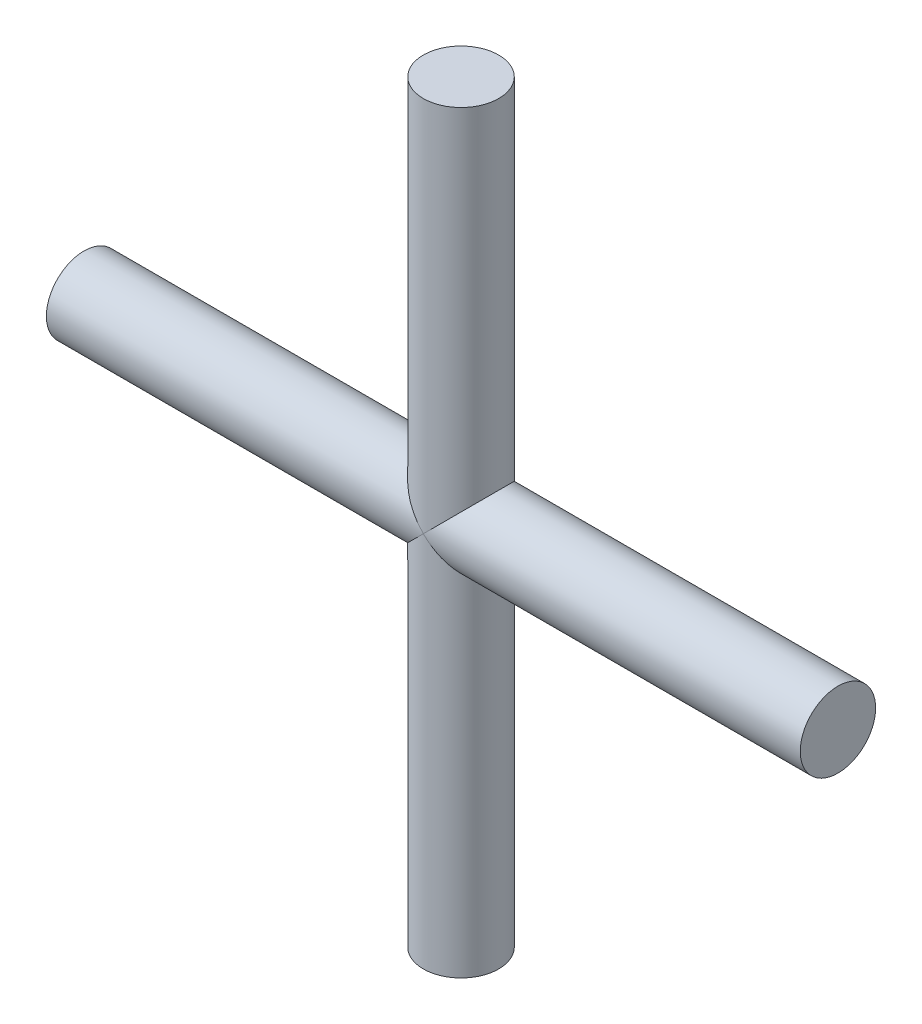
SolidWorks part; units mm, degrees
ref_plane "Front Plane" through (0, 0, 0) normal (0, 0, 1) x (1, 0, 0)
ref_plane "Top Plane" through (0, 0, 0) normal (0, 1, 0) x (1, 0, 0)
ref_plane "Right Plane" through (0, 0, 0) normal (1, 0, 0) x (0, 0, -1)
sketch "Sketch1" plane through (0, 0, 0) normal (0, 1, 0) x (1, 0, 0)
  circle A0 centre (0, 0) radius 0.75
  dimension "D1" = 1.5
extrude "Boss-Extrude1" add sketch "Sketch1" along normal blind 15
sketch "Sketch2" plane through (0, 0, 0) normal (0, 0, 1) x (1, 0, 0)
  line L0 (0, 15) -> (0, 0) construction
  line L1 (0.75, 15) -> (-0.75, 15) construction
  line L2 (-7.5, 7.5) -> (7.5, 7.5) construction
  point P8 (0, 7.5)
  dimension "D1" = 15
ref_plane "Plane1" through (-7.5, 7.5, 0) normal (1, 0, 0) x (0, 0, -1)
sketch "Sketch3" plane through (-7.5, 7.5, 0) normal (1, 0, 0) x (0, 0, -1)
  line L0 (0, 7.5) -> (0, -7.5) construction
  circle A0 centre (0, 0) radius 0.75
  dimension "D1" = 1.5
extrude "Boss-Extrude2" add sketch "Sketch3" along normal blind 15
